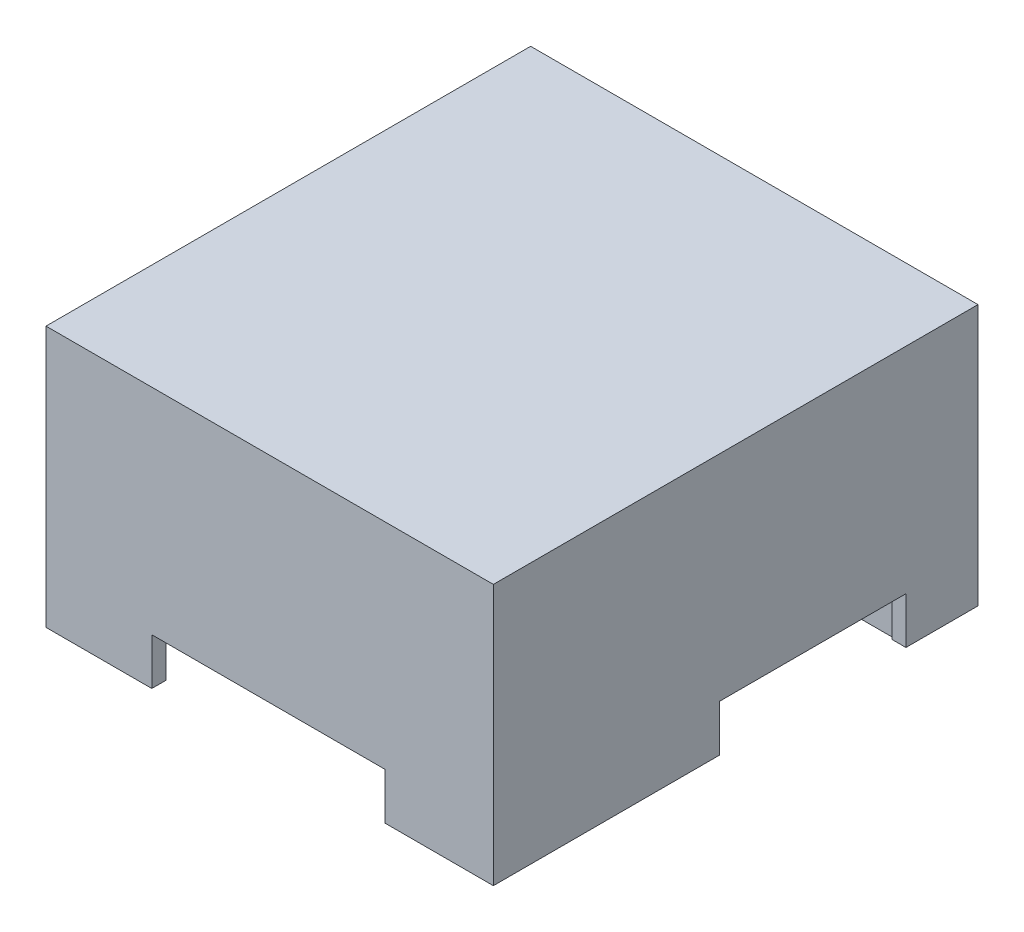
SolidWorks part; units mm, degrees
ref_plane "Front Plane" through (0, 0, 0) normal (0, 0, 1) x (1, 0, 0)
ref_plane "Top Plane" through (0, 0, 0) normal (0, 1, 0) x (1, 0, 0)
ref_plane "Right Plane" through (0, 0, 0) normal (1, 0, 0) x (0, 0, -1)
sketch "Sketch1" plane through (0, 0, 0) normal (0, 1, 0) x (1, 0, 0)
  line L1 (22.5, 24.5) -> (-22.5, 24.5)
  line L2 (22.5, 24.5) -> (22.5, -24.5)
  line L3 (22.5, -24.5) -> (-22.5, -24.5)
  line L4 (-22.5, 24.5) -> (-22.5, -24.5)
  line L5 (22.5, 24.5) -> (-22.5, -24.5) construction
  line L6 (22.5, -24.5) -> (-22.5, 24.5) construction
  line L7 (24, 26) -> (-24, 26)
  line L8 (24, 26) -> (24, -26)
  line L9 (24, -26) -> (-24, -26)
  line L10 (-24, 26) -> (-24, -26)
  line L11 (24, 26) -> (-24, -26) construction
  line L12 (24, -26) -> (-24, 26) construction
  point P0 (0, 0)
  point P6 (0, 0)
  dimension "D1" = 49
  dimension "D2" = 45
  dimension "D3" = 52
  dimension "D4" = 48
extrude "Boss-Extrude1" add sketch "Sketch1" along normal blind 25
sketch "Sketch2" plane through (0, 0, 0) normal (0, 1, 0) x (1, 0, 0)
  line L0 (0, 24.5) -> (0, -24.5) construction
  line L1 (-22.5, 24.5) -> (-16.5, 24.5)
  line L2 (-22.5, 24.5) -> (-22.5, 18.5)
  line L3 (-22.5, 18.5) -> (-16.5, 18.5)
  line L4 (-16.5, 24.5) -> (-16.5, 18.5)
  line L5 (22.5, 24.5) -> (-22.5, 24.5) construction
  line L6 (-22.5, -24.5) -> (22.5, -24.5) construction
  line L7 (-22.5, 0) -> (22.5, 0) construction
  line L8 (-22.5, 24.5) -> (-22.5, -24.5) construction
  line L9 (22.5, -24.5) -> (22.5, 24.5) construction
  line L10 (22.5, 18.5) -> (16.5, 18.5)
  line L11 (16.5, 24.5) -> (16.5, 18.5)
  line L12 (22.5, 24.5) -> (16.5, 24.5)
  line L13 (22.5, 24.5) -> (22.5, 18.5)
  line L14 (22.5, -24.5) -> (22.5, -18.5)
  line L15 (22.5, -24.5) -> (16.5, -24.5)
  line L16 (16.5, -24.5) -> (16.5, -18.5)
  line L17 (22.5, -18.5) -> (16.5, -18.5)
  line L18 (-22.5, -18.5) -> (-16.5, -18.5)
  line L19 (-16.5, -24.5) -> (-16.5, -18.5)
  line L20 (-22.5, -24.5) -> (-16.5, -24.5)
  line L21 (-22.5, -24.5) -> (-22.5, -18.5)
  dimension "D1" = 6
  dimension "D2" = 6
extrude "Boss-Extrude2" add sketch "Sketch2" along normal blind 15
sketch "Sketch3" plane through (0, 0, 0) normal (0, 1, 0) x (1, 0, 0)
  line L0 (0, 24.3738) -> (0, -24.6262) construction
  line L3 (-22.5, -0.1262) -> (22.5, -0.1262) construction
  circle A0 centre (-18.75, 20.6238) radius 1
  circle A1 centre (18.75, 20.6238) radius 1
  circle A2 centre (18.75, -20.8762) radius 1
  circle A3 centre (-18.75, -20.8762) radius 1
  dimension "D1" = 2
extrude "Cut-Extrude1" cut sketch "Sketch3" along normal blind 10
ref_plane "Plane1" through (0, 25, 0) normal (0, 1, 0) x (1, 0, 0)
sketch "Sketch4" plane through (0, 25, 0) normal (0, 1, 0) x (1, 0, 0)
  line L1 (-24, 26) -> (24, 26)
  line L2 (-24, 26) -> (-24, -26)
  line L3 (-24, -26) -> (24, -26)
  line L4 (24, 26) -> (24, -26)
extrude "Boss-Extrude3" add sketch "Sketch4" along normal blind 3
sketch "Sketch5" plane through (0, 0, 26) normal (0, 0, 1) x (1, 0, 0)
  line L0 (-24, 0) -> (24, 0) construction
  line L1 (-12.6486, 0) -> (12.3514, 0)
  line L2 (-12.6486, 0) -> (-12.6486, 5)
  line L3 (-12.6486, 5) -> (12.3514, 5)
  line L4 (12.3514, 0) -> (12.3514, 5)
  dimension "D1" = 25
  dimension "D2" = 5
extrude "Cut-Extrude2" cut sketch "Sketch5" against normal blind 3 contours L2 L1 L4 L3
sketch "Sketch6" plane through (24, 0, 0) normal (1, 0, 0) x (0, 0, -1)
  line L0 (-26, 0) -> (26, 0) construction
  line L1 (18.2668, 0) -> (-1.7332, 0)
  line L2 (18.2668, 0) -> (18.2668, 5)
  line L3 (18.2668, 5) -> (-1.7332, 5)
  line L4 (-1.7332, 0) -> (-1.7332, 5)
  dimension "D1" = 5
  dimension "D2" = 20
extrude "Cut-Extrude3" cut sketch "Sketch6" against normal blind 3 contours L2 L1 L4 L3
sketch "Sketch7" plane through (-24, 0, 0) normal (-1, 0, 0) x (0, 0, 1)
  line L0 (-26, 0) -> (26, 0) construction
  line L1 (-1.8158, 0) -> (18.1842, 0)
  line L2 (-1.8158, 0) -> (-1.8158, 5)
  line L3 (-1.8158, 5) -> (18.1842, 5)
  line L4 (18.1842, 0) -> (18.1842, 5)
  dimension "D1" = 20
  dimension "D2" = 5
extrude "Cut-Extrude4" cut sketch "Sketch7" against normal blind 3 contours L2 L1 L4 L3
